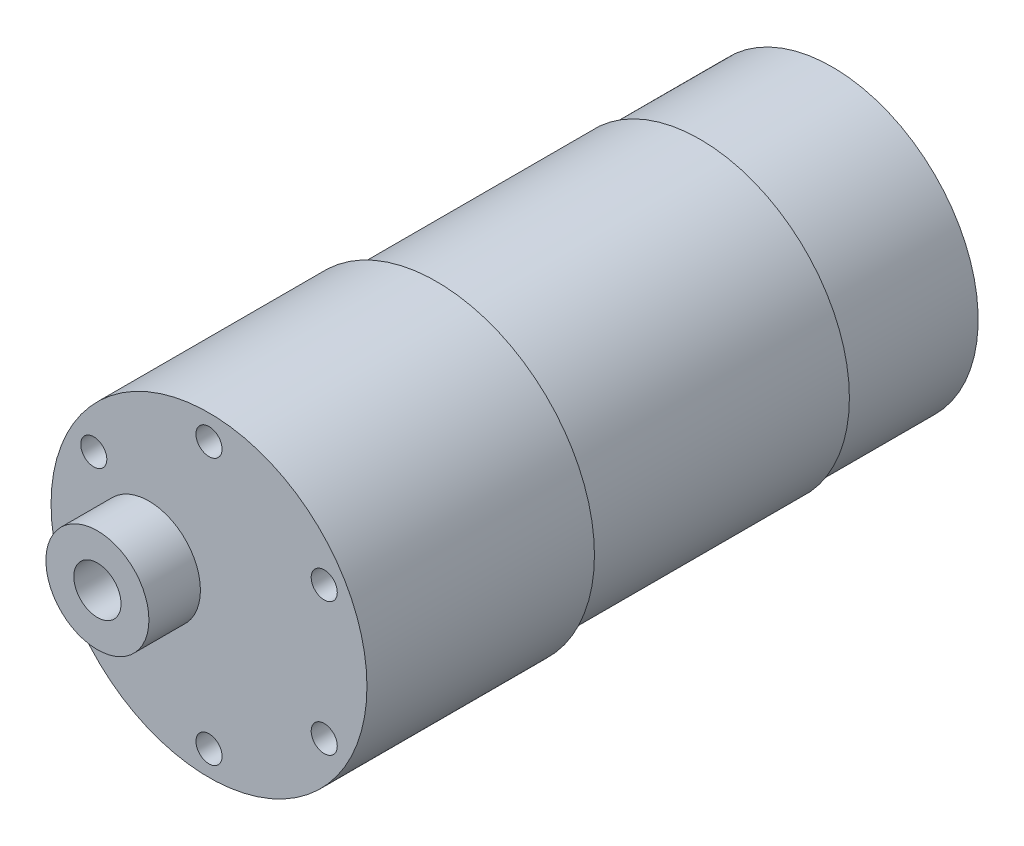
SolidWorks part; units mm, degrees
ref_plane "Front Plane" through (0, 0, 0) normal (0, 0, 1) x (1, 0, 0)
ref_plane "Top Plane" through (0, 0, 0) normal (0, 1, 0) x (1, 0, 0)
ref_plane "Right Plane" through (0, 0, 0) normal (1, 0, 0) x (0, 0, -1)
sketch "S01 - Pololu 4755 brushed motor can" plane through (0, 0, 0) normal (0, 0, 1) x (1, 0, 0)
  circle A0 centre (7, 0) radius 17.4
  dimension "D1" = 34.8
  dimension "D2" = 7
extrude "01 - Pololu 4755 brushed motor can" add sketch "S01 - Pololu 4755 brushed motor can" along normal blind 30.7 from offset 57.2
sketch "S02 - 37D gearbox body" plane through (0, 0, 0) normal (0, 0, 1) x (1, 0, 0)
  circle A0 centre (7, 0) radius 18.4
  dimension "D1" = 36.8
  dimension "D2" = 7
extrude "02 - 37D gearbox body" add sketch "S02 - 37D gearbox body" along normal blind 26.5 from offset 26.5
sketch "S03 - Manufacturer six M3 face threads" plane through (0, 0, 0) normal (0, 0, 1) x (1, 0, 0)
  circle A0 centre (20.4234, 7.75) radius 1.52
  circle A1 centre (7, 15.5) radius 1.52
  circle A2 centre (-6.4234, 7.75) radius 1.52
  circle A3 centre (-6.4234, -7.75) radius 1.52
  circle A4 centre (7, -15.5) radius 1.52
  circle A5 centre (20.4234, -7.75) radius 1.52
  dimension "D1" = 3.04
  dimension "D2" = 3.04
  dimension "D3" = 3.04
  dimension "D4" = 3.04
  dimension "D5" = 3.04
  dimension "D6" = 3.04
  dimension "D7" = 7
  dimension "D8" = 20.4234
  dimension "D9" = 6.4234
  dimension "D10" = 7.75
  dimension "D11" = 15.5
  dimension "D12" = 7.75
  dimension "D13" = 15.5
extrude "03 - Manufacturer six M3 face threads" cut sketch "S03 - Manufacturer six M3 face threads" along normal blind 3.2 from offset 3 offset against normal yes
sketch "S04 - Front locating boss" plane through (0, 0, 0) normal (0, 0, 1) x (1, 0, 0)
  circle A0 centre (0, 0) radius 6
  dimension "D1" = 12
extrude "04 - Front locating boss" add sketch "S04 - Front locating boss" along normal blind 6
sketch "S05 - Quadrature encoder rear cap - 15.4 mm" plane through (0, 0, 0) normal (0, 0, 1) x (1, 0, 0)
  circle A0 centre (7, 0) radius 17
  dimension "D1" = 34
  dimension "D2" = 7
extrude "05 - Quadrature encoder rear cap - 15.4 mm" add sketch "S05 - Quadrature encoder rear cap - 15.4 mm" along normal blind 15.4 from offset 72.6
sketch "S06 - Shaft journal at gearbox output" plane through (0, 0, 0) normal (0, 0, 1) x (1, 0, 0)
  circle A0 centre (0, 0) radius 2.75
  dimension "D1" = 5.5
extrude "06 - Shaft journal at gearbox output" cut sketch "S06 - Shaft journal at gearbox output" along normal blind 4.5 from offset 1.6
